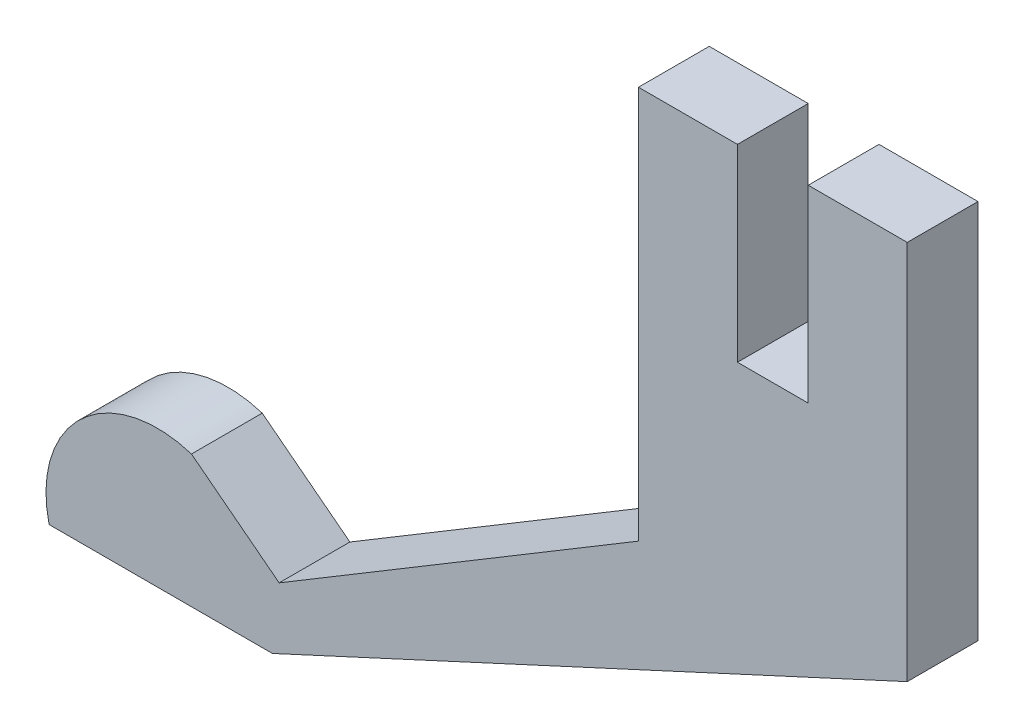
SolidWorks part; units mm, degrees
ref_plane "Front" through (0, 0, 0) normal (0, 0, 1) x (1, 0, 0)
ref_plane "Top" through (0, 0, 0) normal (0, 1, 0) x (1, 0, 0)
ref_plane "Right" through (0, 0, 0) normal (1, 0, 0) x (0, 0, -1)
sketch "Sketch1" plane through (0, 0, 0) normal (0, 0, 1) x (1, 0, 0)
  line L0 (680.4576, 60.2603) -> (676.2606, 60.2603)
  line L1 (680.4576, 44.1323) -> (653.5406, 31.7093)
  line L2 (653.8298, 34.4459) -> (669.0635, 43.5948)
  line L3 (653.5406, 31.7093) -> (644.0787, 31.7093)
  line L4 (653.8298, 34.4459) -> (650.1128, 37.3183)
  line L5 (673.2606, 60.2603) -> (673.2606, 52.2603)
  line L6 (673.2606, 52.2603) -> (676.2606, 52.2603)
  line L7 (676.2606, 52.2603) -> (676.2606, 60.2603)
  line L8 (669.0635, 60.2603) -> (669.0635, 43.5948)
  line L9 (673.2606, 60.2603) -> (669.0635, 60.2603)
  line L10 (680.4576, 44.1323) -> (680.4576, 60.2603)
  arc A0 (650.1128, 37.3183) -> (644.0787, 31.7093) centre (648.6672, 32.8232) ccw
  dimension "D1" = 3
  dimension "D2" = 8
extrude "Base-Extrude" add sketch "Sketch1" along normal blind 3
